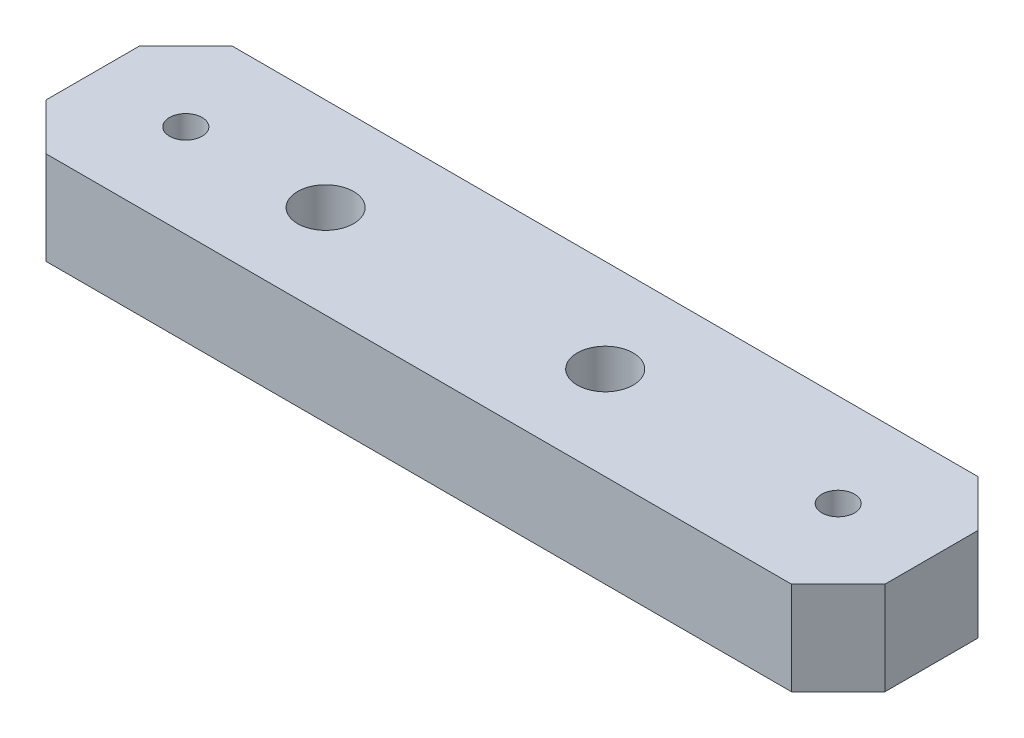
SolidWorks part; units mm, degrees
material "ABS PC"
ref_plane "Спереди" through (0, 0, 0) normal (0, 0, 1) x (1, 0, 0)
ref_plane "Сверху" through (0, 0, 0) normal (0, 1, 0) x (1, 0, 0)
ref_plane "Справа" through (0, 0, 0) normal (1, 0, 0) x (0, 0, -1)
sketch "Sketch1" plane through (0, 0, 0) normal (0, 1, 0) x (1, 0, 0)
  line L1 (-10, 10) -> (80, 10)
  line L2 (-10, 10) -> (-10, -10)
  line L3 (-10, -10) -> (80, -10)
  line L4 (80, 10) -> (80, -10)
  circle A0 centre (0, 0) radius 1.75
  circle A1 centre (70, 0) radius 1.75
  circle A2 centre (15, 0) radius 3
  circle A3 centre (45, 0) radius 3
  point P13 (-10, 0)
  dimension "D1" = 70
  dimension "D3" = 10
  dimension "D4" = 3.5
  dimension "D6" = 6
  dimension "D7" = 15
  dimension "D8" = 30
  dimension "D2" = 20
  dimension "D5" = 90
extrude "Boss-Extrude1" add sketch "Sketch1" along normal blind 10
chamfer "Chamfer1" distance 5 angle 45 4 edges at (-10, 5, -10) (80, 5, -10) (80, 5, 10) (-10, 5, 10)
